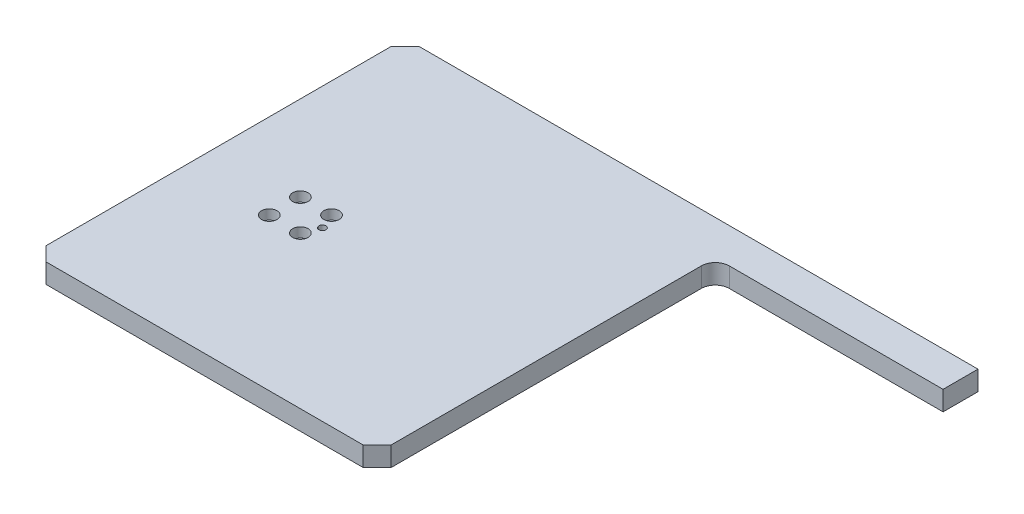
SolidWorks part; units mm, degrees
material "6061-T6 (SS)"
ref_plane "Front Plane" through (0, 0, 0) normal (0, 0, 1) x (1, 0, 0)
ref_plane "Top Plane" through (0, 0, 0) normal (0, 1, 0) x (1, 0, 0)
ref_plane "Right Plane" through (0, 0, 0) normal (1, 0, 0) x (0, 0, -1)
sketch "Sketch1" plane through (0, 0, 0) normal (0, 1, 0) x (1, 0, 0)
  line L0 (337.94, 147) -> (337.94, 122)
  line L1 (337.94, 122) -> (184.94, 122)
  line L2 (174.94, 112) -> (174.94, -110)
  line L3 (164.94, -120) -> (-62.06, -120)
  line L4 (-72.06, 137) -> (-62.06, 147)
  line L5 (-62.06, 147) -> (337.94, 147)
  line L6 (-72.06, 137) -> (-72.06, -110)
  line L7 (-72.06, -120) -> (337.94, -120) construction
  line L8 (337.94, 147) -> (337.94, -120) construction
  line L9 (-72.06, -110) -> (-62.06, -120)
  line L10 (174.94, -110) -> (164.94, -120)
  circle A0 centre (0, 0) radius 20 construction
  arc A1 (184.94, 122) -> (174.94, 112) centre (184.94, 112) ccw
  point P6 (174.94, -120)
  point P7 (-72.06, 147)
  point P14 (174.94, 122)
  dimension "D1" = 40
  dimension "D8" = 10
  dimension "D2" = 267
  dimension "D3" = 410
  dimension "D4" = 163
  dimension "D5" = 25
  dimension "D6" = 174.94
  dimension "D7" = 122
extrude "Boss-Extrude1" add sketch "Sketch1" along normal blind 14
sketch "Sketch2" plane through (0, 0, 0) normal (0, 1, 0) x (1, 0, 0)
  circle A0 centre (0, 0) radius 20
  dimension "D1" = 40
extrude "Cut-Extrude1" cut sketch "Sketch2" along normal blind 2.28
hole_wizard "CBORE for #00 Binding Head Machine Screw1" positions "Sketch3" profile "Sketch4" counterbore size "#00" standard "ANSI Inch" end condition through all
sketch "Sketch3" plane through (0, 14, 0) normal (0, -1, 0) x (-1, 0, 0)
  line L0 (-11.1369, 11.1369) -> (-11.1369, -11.1369) construction
  line L1 (-11.1369, -11.1369) -> (11.1369, -11.1369) construction
  line L3 (11.1369, -11.1369) -> (11.1369, 11.1369) construction
  line L4 (11.1369, 11.1369) -> (-11.1369, 11.1369) construction
  line L6 (11.1369, 11.1369) -> (-11.1369, -11.1369) construction
  point P0 (11.1369, -11.1369)
  point P2 (-11.1369, -11.1369)
  point P4 (-11.1369, 11.1369)
  point P6 (11.1369, 11.1369)
  dimension "D1" = 31.5
sketch "Sketch4" plane through (-11.1369, 14, 11.1369) normal (1, 0, 0) x (0, 0, 1)
  line L0 (0, 0) -> (0, 14)
  line L1 (0, 14) -> (2.25, 14)
  line L3 (2.25, 14) -> (2.25, 7)
  line L4 (2.25, 7) -> (5.5, 7)
  line L5 (5.5, 7) -> (5.5, 0)
  line L7 (5.5, 0) -> (0, 0)
  line L11 (0, -6.35) -> (0, 107.95) construction
  dimension "Thru Hole Dia." = 4.5
  dimension "Thru Hole Depth" = 14
  dimension "C'Bore Dia." = 11
  dimension "C'Bore Depth" = 7
sketch "Sketch5" plane through (0, 2.28, 0) normal (0, -1, 0) x (-1, 0, 0)
  circle A0 centre (-15.75, 0) radius 2.5
  circle A1 centre (0, 0) radius 15.75 construction
  point P6 (11.1369, 11.1369)
  dimension "D1" = 5
extrude "Cut-Extrude2" cut sketch "Sketch5" against normal through all
